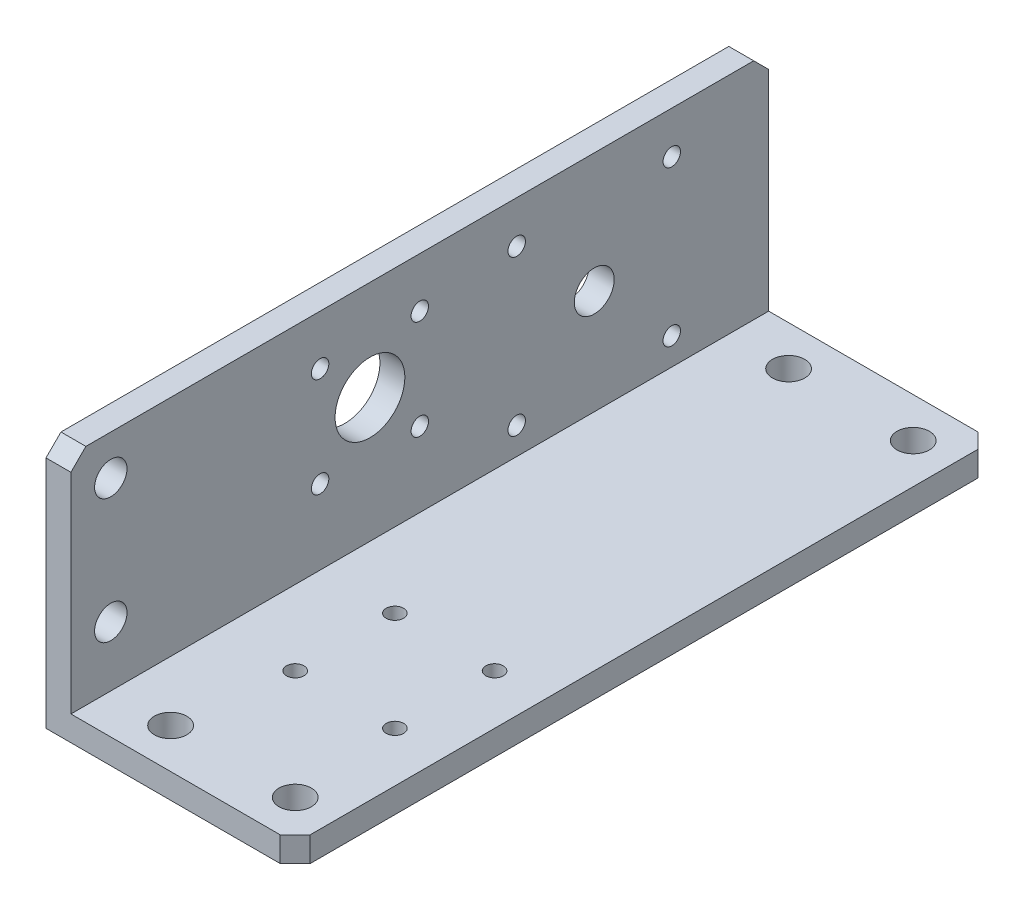
SolidWorks part; units mm, degrees
material "Lega 1060"
ref_plane "Piano frontale" through (0, 0, 0) normal (0, 0, 1) x (1, 0, 0)
ref_plane "Piano superiore" through (0, 0, 0) normal (0, 1, 0) x (1, 0, 0)
ref_plane "Piano destro" through (0, 0, 0) normal (1, 0, 0) x (0, 0, -1)
sketch "Schizzo1" plane through (0, 0, 0) normal (0, 0, 1) x (1, 0, 0)
  line L0 (0, 0) -> (0, 50)
  line L1 (0, 50) -> (5, 50)
  line L2 (5, 50) -> (5, 5)
  line L3 (5, 5) -> (50, 5)
  line L4 (50, 5) -> (50, 0)
  line L5 (50, 0) -> (0, 0)
  dimension "D1" = 5
  dimension "D2" = 5
  dimension "D3" = 50
  dimension "D4" = 50
extrude "Estrusione-Estrusione1" add sketch "Schizzo1" along normal blind 140
sketch "Schizzo2" plane through (0, 0, 0) normal (0, -1, 0) x (1, 0, 0)
  line L0 (5.4524, 132) -> (42.7933, 132) construction
  line L1 (0, 140) -> (50, 140) construction
  line L5 (50, 140) -> (50, 0) construction
  point P4 (17, 132)
  point P5 (42, 132)
  dimension "D1" = 8
  dimension "D2" = 25
  dimension "D3" = 8
sketch "Schizzo3" plane through (0, 0, 0) normal (-1, 0, 0) x (0, 0, 1)
  line L0 (132, 44.621) -> (132, 5.772) construction
  line L1 (140, 50) -> (140, 0) construction
  line L2 (140, 50) -> (0, 50) construction
  point P4 (132, 42)
  point P5 (132, 17)
  dimension "D1" = 8
  dimension "D2" = 8
  dimension "D3" = 25
hole_wizard "Foro Ø6.5 (6.5)-1" positions "Schizzo5" profile "Schizzo4" hole size "Ø6.5" standard "ISO" end condition through all
sketch "Schizzo5" plane through (0, 0, 0) normal (0, -1, 0) x (-1, 0, 0)
  point P0 (-17, -132)
  point P3 (-42, -132)
sketch "Schizzo4" plane through (17, 0, 132) normal (1, 0, 0) x (0, 0, -1)
  line L0 (0, 0) -> (0, 50)
  line L1 (0, 50) -> (3.25, 50)
  line L2 (3.25, 50) -> (3.25, 0)
  line L5 (3.25, 0) -> (0, 0)
  line L11 (0, -6.35) -> (0, 107.95) construction
  dimension "Thru Hole Dia." = 6.5
  dimension "Thru Hole Depth" = 50
hole_wizard "Foro Ø6.5 (6.5)-2" positions "Schizzo7" profile "Schizzo6" hole size "Ø6.5" standard "ISO"
sketch "Schizzo7" plane through (0, 0, 0) normal (-1, 0, 0) x (0, 0, 1)
  point P1 (132, 42)
  point P4 (132, 17)
sketch "Schizzo6" plane through (0, 42, 132) normal (0, 1, 0) x (0, 0, 1)
  line L0 (0, 0) -> (0, 6.9528)
  line L1 (0, 6.9528) -> (3.25, 5)
  line L2 (3.25, 5) -> (3.25, 0)
  line L5 (3.25, 0) -> (0, 0)
  line L10 (0, 6.9528) -> (-3.25, 5) construction
  line L11 (0, -6.35) -> (0, 107.95) construction
  dimension "Hole Dia." = 6.5
  dimension "Hole Depth" = 5
  dimension "Drill Angle" = 118
ref_plane "Piano1" through (0, 0, 70) normal (0, 0, 1) x (1, 0, 0)
mirror "Specchia1" about plane through (0, 0, 70) normal (0, 0, 1) of "Foro Ø6.5 (6.5)-1"
sketch "Schizzo10" plane through (0, 0, 0) normal (-1, 0, 0) x (0, 0, 1)
  line L0 (20.1125, 30) -> (43.2424, 30) construction
  line L1 (80, 42.2663) -> (80, 14.8621) construction
  line L2 (49.1906, 60.8094) -> (80, 30) construction
  line L3 (140, 50) -> (140, 0) construction
  line L5 (140, 50) -> (0, 50) construction
  circle A0 centre (70, 40) radius 1.75
  circle A1 centre (90, 40) radius 1.75
  circle A3 centre (90, 20) radius 1.75
  circle A4 centre (70, 20) radius 1.75
  circle A5 centre (80, 30) radius 7
  point P8 (80, 30)
  point P20 (80, 30)
  dimension "D1" = 3.5
  dimension "D7" = 14
  dimension "D2" = 20
  dimension "D3" = 45
  dimension "D5" = 60
  dimension "D6" = 20
  dimension "D4" = 4
extrude "Taglio-Estrusione3" cut sketch "Schizzo10" against normal up to next
sketch "Schizzo11" plane through (0, 0, 0) normal (0, -1, 0) x (1, 0, 0)
  line L0 (30, 100) -> (14.4837, 100) construction
  line L1 (30, 100) -> (4.5929, 74.5929) construction
  line L3 (50, 140) -> (50, 0) construction
  line L4 (0, 140) -> (50, 140) construction
  circle A0 centre (20, 90) radius 1.75
  circle A3 centre (20, 110) radius 1.75
  circle A4 centre (40, 110) radius 1.75
  circle A5 centre (40, 90) radius 1.75
  point P2 (30, 100)
  point P17 (30, 100)
  dimension "D2" = 3.5
  dimension "D1" = 20
  dimension "D3" = 45
  dimension "D5" = 20
  dimension "D6" = 40
  dimension "D4" = 4
extrude "Taglio-Estrusione4" cut sketch "Schizzo11" against normal up to next
sketch "Schizzo13" plane through (0, 0, 0) normal (-1, 0, 0) x (0, 0, 1)
  line L0 (44.4447, 26) -> (16.261, 26) construction
  line L1 (50.8995, 41.8995) -> (21.4354, 12.4354) construction
  line L2 (140, 0) -> (0, 0) construction
  circle A0 centre (50.5563, 41.5563) radius 1.75
  circle A1 centre (80, 30) radius 7 construction
  circle A3 centre (50.5563, 10.4437) radius 1.75
  circle A4 centre (19.4437, 10.4437) radius 1.75
  circle A5 centre (19.4437, 41.5563) radius 1.75
  circle A6 centre (35, 26) radius 4
  point P8 (35, 26)
  point P19 (35, 26)
  dimension "D2" = 3.5
  dimension "D7" = 8
  dimension "D1" = 45
  dimension "D3" = 22
  dimension "D4" = 4
  dimension "D5" = 26
  dimension "D6" = 45
extrude "Taglio-Estrusione6" cut sketch "Schizzo13" against normal up to next
chamfer "Smusso1" distance 3 angle 45 4 edges at (50, 2.5, 0) (2.5, 50, 0) (50, 2.5, 140) (2.5, 50, 140)
